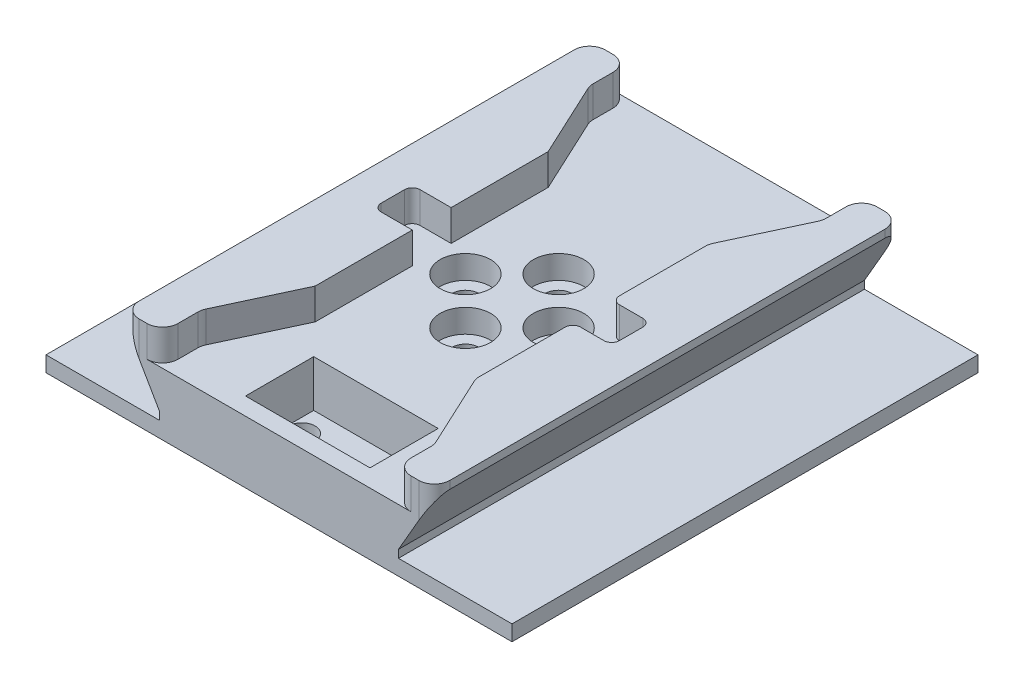
SolidWorks part; units mm, degrees
material "Сплав 2024"
ref_plane "Спереди" through (0, 0, 0) normal (0, 0, 1) x (1, 0, 0)
ref_plane "Сверху" through (0, 0, 0) normal (0, 1, 0) x (1, 0, 0)
ref_plane "Справа" through (0, 0, 0) normal (1, 0, 0) x (0, 0, -1)
sketch "Эскиз1" plane through (0, 0, 0) normal (0, 0, 1) x (1, 0, 0)
  line L0 (-20, 5) -> (-15.3812, -3)
  line L1 (-20, 6) -> (20, 6)
  line L2 (-30, -4) -> (-30, -6)
  line L3 (-30, -6) -> (30, -6)
  line L4 (0, 6) -> (0, -6) construction
  line L5 (30, -4) -> (30, -6)
  line L6 (15.3812, -4) -> (30, -4)
  line L7 (-15.3812, -3) -> (-15.3812, -4)
  line L8 (-15.3812, -4) -> (-30, -4)
  line L9 (-20, 6) -> (-20, 5)
  line L10 (15.3812, -3) -> (15.3812, -4)
  line L11 (20, 5) -> (15.3812, -3)
  line L12 (20, 6) -> (20, 5)
  dimension "D1" = 30
  dimension "D2" = 12
  dimension "D3" = 60
  dimension "D4" = 2
  dimension "D5" = 1
  dimension "D6" = 20
  dimension "D7" = 1
  dimension "D8" = 10
extrude "Бобышка-Вытянуть1" add sketch "Эскиз1" along normal blind 60
sketch "Эскиз2" plane through (0, 6, 0) normal (0, 1, 0) x (1, 0, 0)
  line L0 (0, 0) -> (0, -60) construction
  line L1 (20, 0) -> (-20, 0) construction
  line L2 (20, -60) -> (-20, -60) construction
  line L3 (15, 0) -> (-15, 0)
  line L4 (-15, 0) -> (-15, -5)
  line L5 (-15, -5) -> (-10.3369, -15)
  line L6 (-10.3369, -15) -> (-10.3369, -45)
  line L7 (-10.3369, -45) -> (-15, -55)
  line L8 (-15, -55) -> (-15, -60)
  line L9 (-15, -60) -> (15, -60)
  line L10 (30, -30) -> (-30, -30) construction
  line L11 (30, -60) -> (30, 0) construction
  line L12 (-30, -60) -> (-30, 0) construction
  line L13 (15, -55) -> (15, -60)
  line L14 (10.3369, -45) -> (15, -55)
  line L15 (10.3369, -15) -> (10.3369, -45)
  line L16 (15, -5) -> (10.3369, -15)
  line L17 (15, 0) -> (15, -5)
  point P24 (-10.3369, -30)
  dimension "D1" = 15
  dimension "D2" = 25
  dimension "D3" = 30
  dimension "D5" = 5
  dimension "D6" = 5
extrude "Вырез-Вытянуть1" cut sketch "Эскиз2" against normal blind 4
sketch "Эскиз3" plane through (0, 6, 0) normal (0, 1, 0) x (1, 0, 0)
  line L0 (30, -30) -> (-30, -30) construction
  line L1 (30, -60) -> (30, 0) construction
  line L2 (-30, -60) -> (-30, 0) construction
  line L4 (-10.3369, -27.5) -> (-15.3369, -27.5)
  line L5 (-10.3369, -27.5) -> (-10.3369, -32.5)
  line L6 (-10.3369, -32.5) -> (-15.3369, -32.5)
  line L7 (-15.3369, -27.5) -> (-15.3369, -32.5)
  line L8 (0, 0) -> (0, -60) construction
  line L9 (15, 0) -> (-15, 0) construction
  line L10 (-15, -60) -> (15, -60) construction
  line L11 (10.3369, -27.5) -> (10.3369, -32.5)
  line L12 (10.3369, -32.5) -> (15.3369, -32.5)
  line L13 (15.3369, -27.5) -> (15.3369, -32.5)
  line L14 (10.3369, -27.5) -> (15.3369, -27.5)
  line L15 (-10.3369, -15) -> (-10.3369, -45) construction
  point P12 (-10.3369, -30)
  dimension "D1" = 5
  dimension "D2" = 5
extrude "Вырез-Вытянуть2" cut sketch "Эскиз3" against normal blind 4
fillet "Скругление1" radius 2 14 edges at (20, 5.5, 0) (20, 5.5, 60) (-20, 5.5, 60) (-20, 5.5, 0) (10.3369, 4, 45) (15, 4, 55) (-15, 4, 55) (-15, 4, 5) (10.3369, 4, 15) (15, 4, 5) (15, 4, 0) (-15, 4, 0) (15, 4, 60) (-15, 4, 60)
fillet "Скругление2" radius 1 6 edges at (-15.3369, 4, 27.5) (-15.3369, 4, 32.5) (15.3369, 4, 32.5) (10.3369, 4, 32.5) (15.3369, 4, 27.5) (10.3369, 4, 27.5)
sketch "Эскиз4" plane through (0, 2, 0) normal (0, 1, 0) x (1, 0, 0)
  line L0 (0, 0) -> (0, -60) construction
  line L1 (-17, -60) -> (17, -60) construction
  line L2 (30, -30) -> (-30, -30) construction
  line L3 (30, -60) -> (30, 0) construction
  line L4 (-30, -60) -> (-30, 0) construction
  circle A0 centre (0, -30) radius 6 construction
  dimension "D1" = 12
hole_wizard "Цековка для винта с внутренним шестигранником M31" positions "Эскиз6" profile "Эскиз5" counterbore size "M3" standard "Ansi Metric" end condition through all
sketch "Эскиз6" plane through (0, 2, 0) normal (0, 1, 0) x (1, 0, 0)
  line L0 (0, 0) -> (0, -60) construction
  line L1 (30, -30) -> (-30, -30) construction
  circle A0 centre (0, -30) radius 6 construction
  point P0 (0, -24)
  point P2 (6, -30)
  point P4 (0, -36)
  point P6 (-6, -30)
sketch "Эскиз5" plane through (0, 2, 24) normal (1, 0, 0) x (0, 0, 1)
  line L0 (0, 0) -> (0, 8)
  line L1 (0, 8) -> (1.7, 8)
  line L3 (1.7, 8) -> (1.7, 3)
  line L4 (1.7, 3) -> (3.25, 3)
  line L5 (3.25, 3) -> (3.25, 0)
  line L7 (3.25, 0) -> (0, 0)
  line L11 (0, -6.35) -> (0, 107.95) construction
  dimension "Диаметр сквозного отверстия" = 3.4
  dimension "Глубина сквозного отверстия" = 8
  dimension "Диаметр цековки" = 6.5
  dimension "Глубина цековки" = 3
sketch "Эскиз7" plane through (0, -6, 0) normal (0, -1, 0) x (1, 0, 0)
  line L1 (-30, 45) -> (-70, 45)
  line L2 (-30, 45) -> (-30, 15)
  line L3 (-30, 15) -> (-70, 15)
  line L4 (-70, 45) -> (-70, 15)
  line L5 (30, 30) -> (-70, 30) construction
  line L6 (30, 60) -> (30, 0) construction
  line L7 (-30, 60) -> (-30, 0) construction
  dimension "D1" = 40
  dimension "D2" = 30
extrude "Бобышка-Вытянуть2" [suppressed] add sketch "Эскиз7" against normal blind 6
fillet "Скругление3" [suppressed] radius 5
sketch "Эскиз8" [suppressed] plane through (0, -4, 0) normal (0, 1, 0) x (1, 0, 0)
  line L1 (-70, -45) -> (-70, -15) construction
  line L3 (30, -30) -> (-70, -30) construction
  line L4 (30, -60) -> (30, 0) construction
  line L5 (-30, -45) -> (-70, -45) construction
  line L6 (-68, -20) -> (-30, -20)
  line L7 (-68, -20) -> (-68, -40)
  line L8 (-68, -40) -> (-30, -40)
  line L9 (-30, -20) -> (-30, -40)
  line L10 (-68, -20) -> (-30, -40) construction
  line L11 (-68, -40) -> (-30, -20) construction
  line L12 (-30, -10) -> (-30, -5) construction
  point P0 (-49, -30)
  dimension "D1" = 2
  dimension "D2" = 5
extrude "Вырез-Вытянуть3" [suppressed] cut sketch "Эскиз8" against normal blind 4
sketch "Эскиз9" plane through (0, 2, 0) normal (0, 1, 0) x (1, 0, 0)
  line L1 (-6.5643, -48.9682) -> (9.4628, -48.9682)
  line L2 (-6.5643, -48.9682) -> (-6.5643, -57.7489)
  line L3 (-6.5643, -57.7489) -> (9.4628, -57.7489)
  line L4 (9.4628, -48.9682) -> (9.4628, -57.7489)
extrude "Вырез-Вытянуть4" cut sketch "Эскиз9" against normal blind 6
sketch "Эскиз10" plane through (0, -4, 0) normal (0, 1, 0) x (1, 0, 0)
  circle A0 centre (-4.7497, -52.3058) radius 1.701
extrude "Вырез-Вытянуть5" cut sketch "Эскиз10" against normal through all
